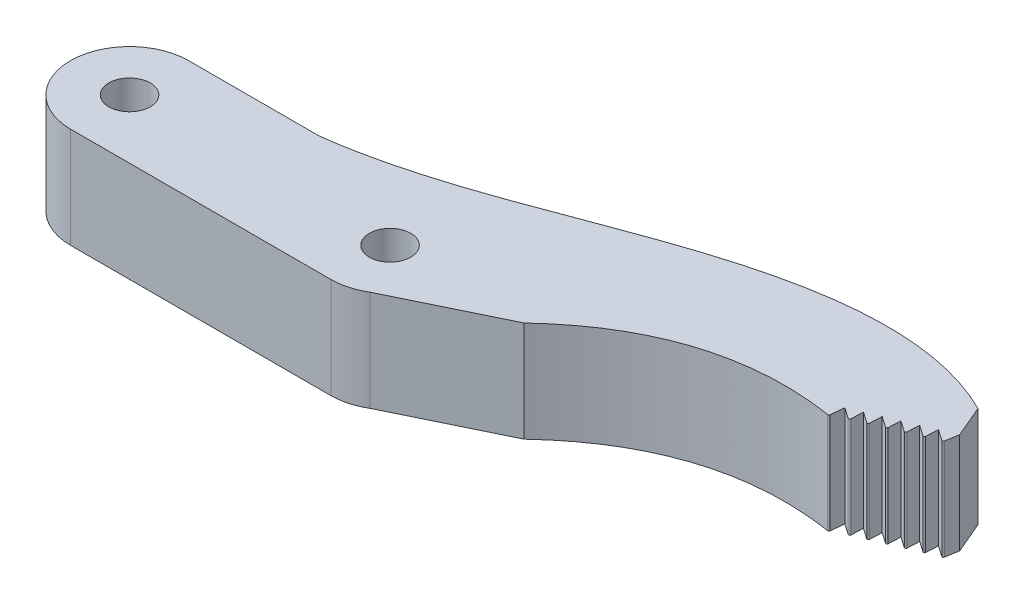
SolidWorks part; units mm, degrees
ref_plane "Front Plane" through (0, 0, 0) normal (0, 0, 1) x (1, 0, 0)
ref_plane "Top Plane" through (0, 0, 0) normal (0, 1, 0) x (1, 0, 0)
ref_plane "Right Plane" through (0, 0, 0) normal (1, 0, 0) x (0, 0, -1)
sketch "Sketch1" plane through (0, 0, 0) normal (0, 1, 0) x (1, 0, 0)
  line L0 (0, 5) -> (22, 5)
  line L1 (0, -5) -> (22, -5)
  arc A0 (0, 5) -> (0, -5) centre (0, 0) ccw
  circle A1 centre (0, 0) radius 1.75
  arc A2 (22, -5) -> (22, 5) centre (22, 0) ccw
  circle A3 centre (22, 0) radius 1.75
  dimension "D1" = 10
  dimension "D2" = 10
  dimension "D3" = 3.5
  dimension "D4" = 3.5
  dimension "D5" = 22
extrude "Boss-Extrude1" add sketch "Sketch1" along normal blind 8.5
sketch "Sketch2" plane through (0, 8.5, 0) normal (0, 1, 0) x (1, 0, 0)
  line L0 (-14.2211, -5) -> (58.2211, -5) construction
  line L1 (0.8335, -15.812) -> (45.3665, 5.812) construction
  line L2 (24.179, -4.4761) -> (33.3416, -0.027)
  line L3 (26.82, -5) -> (49.9329, 4.7965) construction
  line L4 (52.969, 6.0834) -> (60.3347, 9.2054)
  line L5 (60.3347, 9.2054) -> (58.7737, 12.8883)
  line L6 (22, 5) -> (0, 5) construction
  line L7 (11, 5) -> (22, 5)
  arc A0 (22, 5) -> (24.179, -4.4761) centre (22, 0.0114) cw
  spline S0 degree 2 poles (33.3416, -0.027) (41.7498, 7.8931) (52.969, 6.0834) knots 0 0 0 1 1 1
  spline S1 degree 3 poles (58.7737, 12.8883) (52.7742, 15.8908) (35.6036, 14.5978) (21.1528, 6.296) (11, 5) knots 0 0 0 0 0.392136 1 1 1 1
  point P4 (22, -5)
  point P6 (23.1, -5)
  dimension "D8" = 21.36
  dimension "D9" = 49.5888
  dimension "D1" = 25.9
  dimension "D2" = 1.1
  dimension "D3" = 4.82
  dimension "D4" = 22.97
  dimension "D5" = 28.79
  dimension "D6" = 8
  dimension "D7" = 4
extrude "Boss-Extrude2" add sketch "Sketch2" against normal blind 8.5
sketch "Sketch3" plane through (0, 8.5, 0) normal (0, 1, 0) x (1, 0, 0)
  line L0 (49.766, 5.9088) -> (60.7452, 10.5624) construction
  line L1 (52.969, 6.0834) -> (60.3347, 9.2054) construction
  line L2 (52.969, 6.0834) -> (53.0936, 7.3192)
  line L3 (53.0936, 7.3192) -> (54.1587, 6.5877)
  line L4 (54.1587, 6.5877) -> (54.1993, 7.7879)
  line L5 (54.1993, 7.7879) -> (55.2556, 7.0526)
  line L6 (55.2556, 7.0526) -> (55.3115, 8.2593)
  line L7 (55.3115, 8.2593) -> (56.3678, 7.524)
  line L8 (56.3678, 7.524) -> (56.4237, 8.7307)
  line L9 (56.4237, 8.7307) -> (57.48, 7.9955)
  line L10 (57.48, 7.9955) -> (57.5359, 9.2021)
  line L11 (57.5359, 9.2021) -> (58.5922, 8.4669)
  line L12 (58.5922, 8.4669) -> (58.6481, 9.6736)
  line L13 (58.6481, 9.6736) -> (59.7044, 8.9383)
  line L14 (59.7044, 8.9383) -> (59.9096, 10.2083)
  line L15 (52.969, 6.0834) -> (60.3347, 9.2054)
  line L16 (60.3347, 9.2054) -> (59.9096, 10.2083)
  line M7 (52.969, 6.0834) -> (60.3347, 9.2054)
  line M8 (60.3347, 9.2054) -> (58.7737, 12.8883)
  dimension "D1" = 1.0892
  dimension "D2" = 61.273
extrude "Cut-Extrude1" cut sketch "Sketch3" against normal blind 8.5 contours L3 L2 M7 | L5 L4 M7 | L7 L6 M7 | L9 L8 M7 | L11 L10 M7 | L13 L12 M7 | L14 M7 M8
fillet "Fillet1" radius 0.1 7 edges at (59.7044, 4.25, -8.9383) (58.5922, 4.25, -8.4669) (57.48, 4.25, -7.9955) (56.3678, 4.25, -7.524) (55.2556, 4.25, -7.0526) (54.1587, 4.25, -6.5877) (52.969, 4.25, -6.0834)
